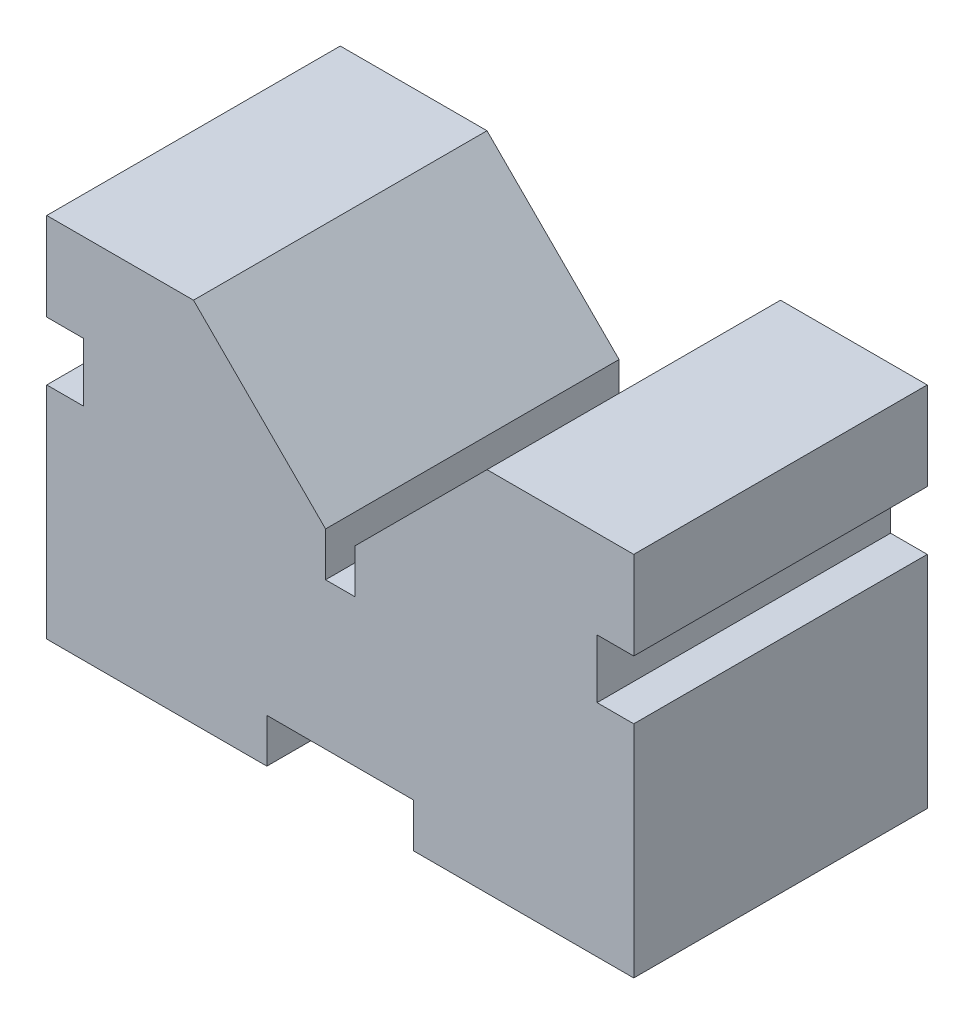
SolidWorks part; units mm, degrees
ref_plane "前视基准面" through (0, 0, 0) normal (0, 0, 1) x (1, 0, 0)
ref_plane "上视基准面" through (0, 0, 0) normal (0, 1, 0) x (1, 0, 0)
ref_plane "右视基准面" through (0, 0, 0) normal (1, 0, 0) x (0, 0, -1)
sketch "草图1" plane through (0, 0, 0) normal (0, 1, 0) x (1, 0, 0)
  line L0 (-40, 20) -> (40, 20)
  line L1 (40, 20) -> (40, -20)
  line L2 (40, -20) -> (-40, -20)
  line L3 (-40, -20) -> (-40, 20)
extrude "凸台-拉伸1" add sketch "草图1" along normal blind 50
sketch "草图2" plane through (0, 0, 0) normal (0, 0, 1) x (1, 0, 0)
  line L0 (-20, 50) -> (20, 50)
  line L1 (20, 50) -> (2, 32)
  line L2 (2, 32) -> (2, 26)
  line L3 (2, 26) -> (-2, 26)
  line L4 (-2, 26) -> (-2, 32)
  line L5 (-2, 32) -> (-20, 50)
extrude "切除-拉伸1" cut sketch "草图2" against normal mid plane 162
sketch "草图3" plane through (0, 0, 0) normal (0, 0, 1) x (1, 0, 0)
  line L0 (-10, 0) -> (10, 0)
  line L1 (10, 0) -> (10, 6)
  line L2 (10, 6) -> (-10, 6)
  line L3 (-10, 6) -> (-10, 0)
extrude "切除-拉伸2" cut sketch "草图3" against normal mid plane 162
sketch "草图4" plane through (0, 0, 0) normal (0, 0, 1) x (1, 0, 0)
  line L0 (-40, 30) -> (-35, 30)
  line L1 (-35, 30) -> (-35, 38)
  line L2 (-35, 38) -> (-40, 38)
  line L3 (-40, 38) -> (-40, 30)
  line L4 (35, 30) -> (40, 30)
  line L5 (40, 30) -> (40, 38)
  line L6 (40, 38) -> (35, 38)
  line L7 (35, 38) -> (35, 30)
extrude "切除-拉伸3" cut sketch "草图4" against normal mid plane 162
